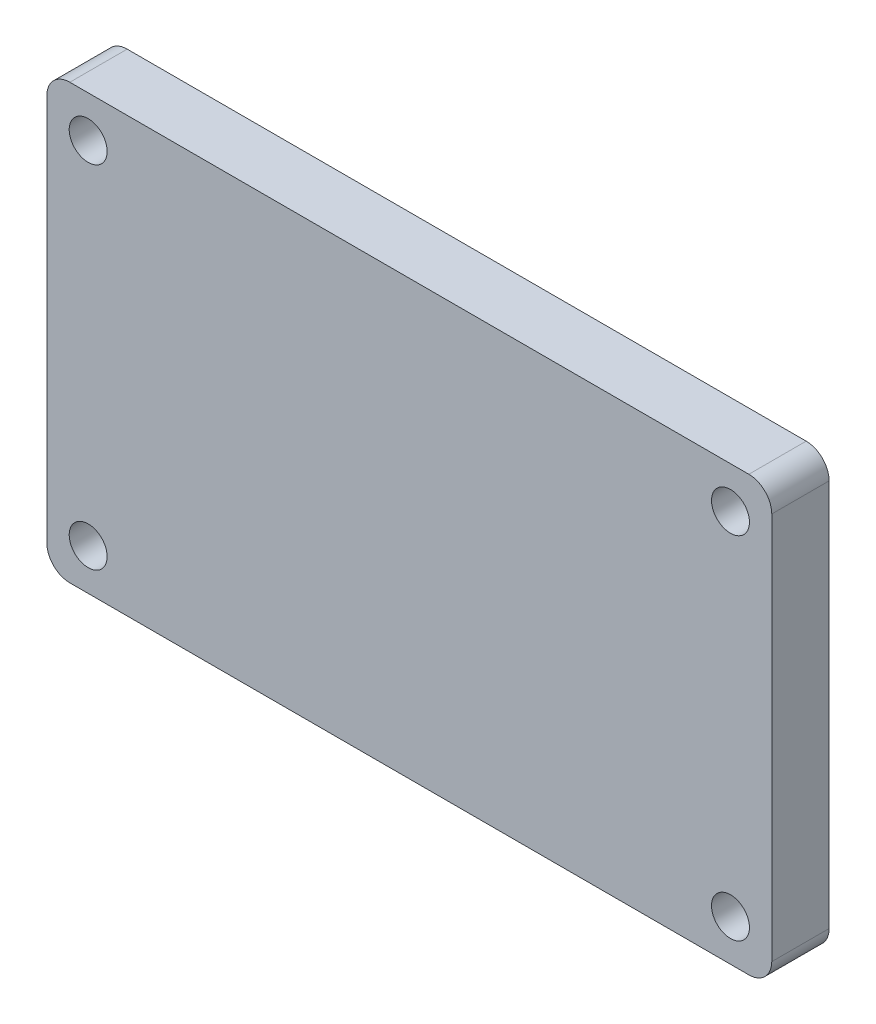
SolidWorks part; units mm, degrees
material "ABS"
ref_plane "X-Y Datum" through (0, 0, 0) normal (0, 0, 1) x (1, 0, 0)
ref_plane "X-Z Datum" through (0, 0, 0) normal (0, 1, 0) x (1, 0, 0)
ref_plane "Y-Z Datum" through (0, 0, 0) normal (1, 0, 0) x (0, 0, -1)
sketch "Sketch1" plane through (0, 0, 0) normal (0, 0, 1) x (1, 0, 0)
  line L1 (-40.132, -24.003) -> (40.132, -24.003)
  line L2 (-40.132, -24.003) -> (-40.132, 24.003)
  line L3 (-40.132, 24.003) -> (40.132, 24.003)
  line L4 (40.132, -24.003) -> (40.132, 24.003)
  line L5 (-40.132, -24.003) -> (40.132, 24.003) construction
  line L6 (-40.132, 24.003) -> (40.132, -24.003) construction
  line L7 (-35.56, -19.431) -> (35.56, -19.431)
  line L8 (-35.56, -19.431) -> (-35.56, 19.431)
  line L9 (-35.56, 19.431) -> (35.56, 19.431)
  line L10 (35.56, -19.431) -> (35.56, 19.431)
  line L11 (-35.56, -19.431) -> (35.56, 19.431) construction
  line L12 (-35.56, 19.431) -> (35.56, -19.431) construction
  point P0 (0, 0)
  point P6 (0, 0)
  dimension "D1" = 48.006
  dimension "D2" = 80.264
extrude "Boss-Extrude1" add sketch "Sketch1" along normal blind 6.35 contours L7 L10 L9 L8 | L1 L4 L3 L2 L10 L7 L8 L9
sketch "Sketch2" plane through (0, 0, 6.35) normal (0, 0, 1) x (1, 0, 0)
  line L0 (-40.132, -24.003) -> (40.132, 24.003) construction
  line L1 (-35.56, -19.431) -> (35.56, -19.431)
  line L2 (-35.56, -19.431) -> (-35.56, 19.431)
  line L3 (-35.56, 19.431) -> (35.56, 19.431)
  line L4 (35.56, -19.431) -> (35.56, 19.431)
  line L5 (-35.56, -19.431) -> (35.56, 19.431) construction
  line L6 (-35.56, 19.431) -> (35.56, -19.431) construction
  circle A0 centre (-35.56, 19.431) radius 2.1
  circle A1 centre (-35.56, -19.431) radius 2.1
  circle A2 centre (35.56, 19.431) radius 2.1
  circle A3 centre (35.56, -19.431) radius 2.1
  point P9 (0, 0)
extrude "Cut-Extrude2" cut sketch "Sketch2" against normal through all contours L3 A0 L2 | L2 A0 L3 | L2 A1 L1 | L1 A1 L2 | L4 A2 L3 | L3 A2 L4 | L1 A3 L4 | L4 A3 L1
fillet "Fillet1" radius 2.54 4 edges at (40.132, -24.003, 3.175) (40.132, 24.003, 3.175) (-40.132, -24.003, 3.175) (-40.132, 24.003, 3.175)
